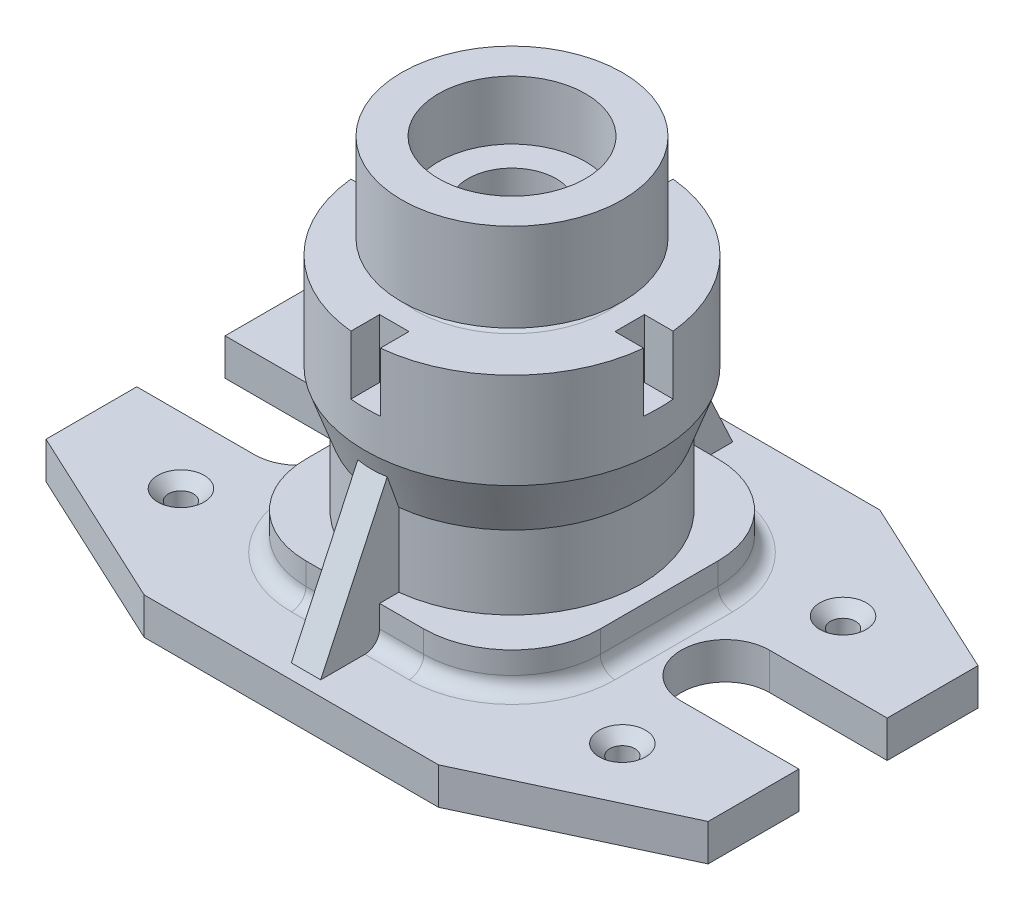
SolidWorks part; units mm, degrees
ref_plane "Front Plane" through (0, 0, 0) normal (0, 0, 1) x (1, 0, 0)
ref_plane "Top Plane" through (0, 0, 0) normal (0, 1, 0) x (1, 0, 0)
ref_plane "Right Plane" through (0, 0, 0) normal (1, 0, 0) x (0, 0, -1)
sketch "Sketch2" plane through (0, 0, 0) normal (0, 1, 0) x (1, 0, 0)
  line L0 (-53.712, 0) -> (58.3324, 0) construction
  line L1 (0, 51.4018) -> (0, -49.4767) construction
  line L2 (-20, 30) -> (20, 30)
  line L3 (20, 30) -> (45, 18.3423)
  line L4 (45, 18.3423) -> (45, 6)
  line L5 (45, 6) -> (29, 6)
  line L6 (29, -6) -> (45, -6)
  line L7 (45, -6) -> (45, -18.3423)
  line L8 (45, -18.3423) -> (20, -30)
  line L9 (20, -30) -> (-20, -30)
  line L10 (-20, -30) -> (-45, -18.3423)
  line L11 (-45, -18.3423) -> (-45, -6)
  line L12 (-45, -6) -> (-29, -6)
  line L13 (-29, 6) -> (-45, 6)
  line L14 (-45, 6) -> (-45, 18.3423)
  line L15 (-45, 18.3423) -> (-20, 30)
  arc A0 (29, 6) -> (29, -6) centre (29, 0) ccw
  arc A1 (-29, -6) -> (-29, 6) centre (-29, 0) ccw
  dimension "D7" = 6
  dimension "D11" = 6
  dimension "D1" = 40
  dimension "D2" = 20
  dimension "D3" = 25
  dimension "D4" = 25
  dimension "D5" = 16
  dimension "D6" = 12
  dimension "D8" = 25
  dimension "D9" = 16
  dimension "D10" = 12
  dimension "D12" = 60
  dimension "D13" = 25
  dimension "D14" = 25
  dimension "D15" = 25
  dimension "D16" = 30
extrude "Boss-Extrude1" add sketch "Sketch2" along normal blind 5
sketch "Sketch3" plane through (0, 5, 0) normal (0, 1, 0) x (1, 0, 0)
  line L0 (0, 35.681) -> (0, -36.8224) construction
  line L1 (-55.7057, 0) -> (61.0999, 0) construction
  point P5 (30, -15)
  point P6 (30, 15)
  point P7 (-30, -15)
  point P8 (-30, 15)
  dimension "D1" = 15
  dimension "D2" = 30
hole_wizard "CSK for M3 Countersunk Flat Head Screw1" positions "Sketch3" profile "Sketch4" countersink size "M3" standard "ISO" end condition through all
sketch "Sketch4" plane through (-30, 5, -15) normal (1, 0, 0) x (0, 0, 1)
  line L0 (0, 0) -> (0, 5)
  line L1 (0, 5) -> (1.7, 5)
  line L2 (1.7, 5) -> (1.7, 1.45)
  line L3 (1.7, 1.45) -> (3.15, 0)
  line L5 (3.15, 0) -> (0, 0)
  line L6 (-1.7, 1.45) -> (-3.15, 0) construction
  line L11 (0, -6.35) -> (0, 107.95) construction
  dimension "Thru Hole Dia." = 3.4
  dimension "Thru Hole Depth" = 5
  dimension "Near C'Sink Dia." = 6.3
  dimension "Near C'Sink Angle" = 90
sketch "Sketch6" plane through (0, 5, 0) normal (0, 1, 0) x (1, 0, 0)
  line L0 (0, 38.8682) -> (0, -49.0261) construction
  line L1 (-57.7732, 0) -> (59.8894, 0) construction
  line L3 (-8, -20) -> (8, -20)
  line L4 (-20, -8) -> (-20, 8)
  line L5 (-8, 20) -> (8, 20)
  line L6 (20, -8) -> (20, 8)
  line L7 (-20, -20) -> (20, 20) construction
  line L8 (-20, 20) -> (20, -20) construction
  arc A0 (-8, -20) -> (-20, -8) centre (-8, -8) cw
  arc A1 (8, -20) -> (20, -8) centre (8, -8) ccw
  arc A2 (20, 8) -> (8, 20) centre (8, 8) ccw
  arc A3 (-8, 20) -> (-20, 8) centre (-8, 8) ccw
  point P5 (0, 0)
  dimension "D3" = 12
  dimension "D1" = 40
  dimension "D2" = 40
extrude "Boss-Extrude2" add sketch "Sketch6" along normal blind 5
fillet "Fillet1" radius 2 8 edges at (0, 5, -20) (16.4853, 5, -16.4853) (20, 5, 0) (16.4853, 5, 16.4853) (0, 5, 20) (-16.4853, 5, 16.4853) (-20, 5, 0) (-16.4853, 5, -16.4853)
sketch "Sketch8" plane through (0, 0, 0) normal (0, -1, 0) x (1, 0, 0)
  circle A0 centre (0, 0) radius 8
  dimension "D1" = 16
extrude "Cut-Extrude1" cut sketch "Sketch8" against normal through all
sketch "Sketch9" plane through (0, 0, 0) normal (0, 0, 1) x (1, 0, 0)
  line L0 (0, -7.6027) -> (0, 66.3973) construction
  line L1 (-8, 10) -> (-17.5, 10)
  line L3 (-8, 10) -> (-8, 28)
  line L4 (-8, 28) -> (-6, 34)
  line L5 (-6, 34) -> (-6, 46)
  line L6 (-6, 46) -> (-10, 46)
  line L7 (-10, 46) -> (-10, 54)
  line L8 (-8, 10) -> (-20, 10) construction
  line L9 (-17.5, 10) -> (-17.5, 20)
  line L10 (-17.5, 20) -> (-20, 27)
  line L11 (-20, 27) -> (-20, 40)
  line L12 (-20, 40) -> (-13.1, 40)
  line L13 (-13.1, 42) -> (-15, 42)
  line L14 (-15, 42) -> (-15, 54)
  line L15 (-15, 54) -> (-10, 54)
  arc A0 (-13.1, 40) -> (-13.1, 42) centre (-13.1, 41) ccw
  dimension "D12" = 1
  dimension "D1" = 18
  dimension "D2" = 6
  dimension "D3" = 12
  dimension "D4" = 54
  dimension "D5" = 17.5
  dimension "D6" = 10
  dimension "D7" = 7
  dimension "D8" = 10
  dimension "D9" = 6
  dimension "D10" = 13
  dimension "D11" = 2
  dimension "D13" = 1.9
  dimension "D14" = 15
  dimension "D15" = 20
revolve "Revolve1" add sketch "Sketch9" angle 360 about L0
sketch "Sketch10" plane through (0, 0, 0) normal (1, 0, 0) x (0, 0, -1)
  line L0 (-30, 5) -> (-18.3423, 5) construction
  line L1 (-28, 5) -> (-19.0203, 24.2569)
  line L2 (-20, 27) -> (-17.5, 20) construction
  point P0 (-28, 5)
  dimension "D1" = 2
  dimension "D2" = 65
rib "Rib1" sketch "Sketch10" sketch "Sketch10" thickness 4 extrusion direction parallel to sketch draft on no parameters "D1"=4
mirror "Mirror1" about plane through (0, 0, 0) normal (0, 0, 1) of "Rib1"
sketch "Sketch11" plane through (0, 40, 0) normal (0, 1, 0) x (1, 0, 0)
  line L0 (0, 34.9436) -> (0, -38.2031) construction
  line L1 (20, -8) -> (20, 8) construction
  line L2 (16, -2) -> (20, -2)
  line L3 (16, -2) -> (16, 2)
  line L4 (16, 2) -> (20, 2)
  line L5 (20, -2) -> (20, 2)
  circle A0 centre (0, 0) radius 20 construction
  point P3 (16, 0)
  dimension "D1" = 16
  dimension "D2" = 4
  dimension "D3" = 2
  dimension "D4" = 4
extrude "Cut-Extrude2" cut sketch "Sketch11" against normal blind 8
pattern_circular "CirPattern1" count 4 every 90 about axis through (0, 0, 0) along (0, 1, 0) of "Cut-Extrude2"
